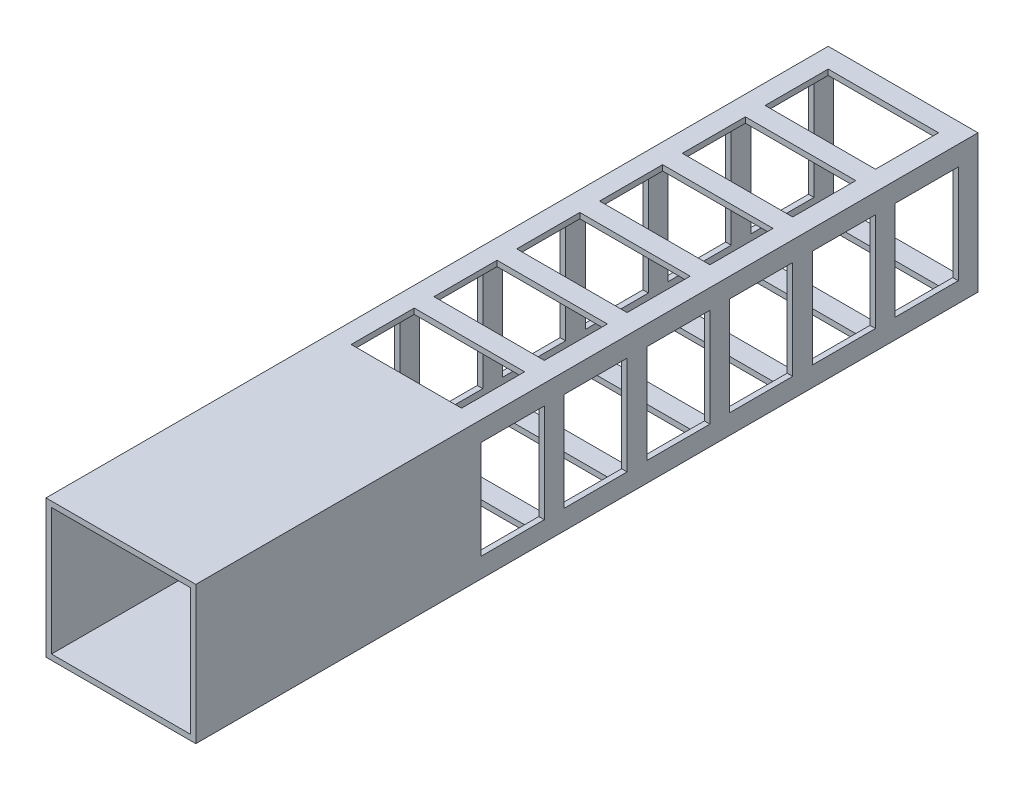
SolidWorks part; units mm, degrees
ref_plane "Front Plane" through (0, 0, 0) normal (0, 0, 1) x (1, 0, 0)
ref_plane "Top Plane" through (0, 0, 0) normal (0, 1, 0) x (1, 0, 0)
ref_plane "Right Plane" through (0, 0, 0) normal (1, 0, 0) x (0, 0, -1)
sketch "Sketch1" plane through (0, 0, 0) normal (0, 0, 1) x (1, 0, 0)
  line L0 (-88, 87.5) -> (88, 87.5)
  line L1 (-95, 94.5) -> (95, 94.5)
  line L2 (-95, 94.5) -> (-95, -80.5)
  line L3 (-95, -80.5) -> (95, -80.5)
  line L4 (95, 94.5) -> (95, -80.5)
  line L5 (88, 87.5) -> (88, -73.5)
  line L6 (-88, -73.5) -> (88, -73.5)
  line L7 (-88, 87.5) -> (-88, -73.5)
  dimension "D3" = 7
extrude "Boss-Extrude1" add sketch "Sketch1" along normal mid plane 992
ref_plane "Plane1" through (95, 0, 0) normal (1, 0, 0) x (0, 0, -1)
sketch "Sketch2" plane through (95, 0, 0) normal (1, 0, 0) x (0, 0, -1)
  line L0 (-496, -80.5) -> (496, -80.5) construction
  line L1 (391, 69.5) -> (471, 69.5)
  line L2 (391, 69.5) -> (391, -55.5)
  line L3 (391, -55.5) -> (471, -55.5)
  line L4 (471, 69.5) -> (471, -55.5)
  line L5 (496, -80.5) -> (496, 94.5) construction
  line L6 (286, 69.5) -> (286, -55.5)
  line L7 (286, 69.5) -> (366, 69.5)
  line L8 (366, 69.5) -> (366, -55.5)
  line L9 (286, -55.5) -> (366, -55.5)
  line L10 (181, 69.5) -> (181, -55.5)
  line L11 (181, 69.5) -> (261, 69.5)
  line L12 (261, 69.5) -> (261, -55.5)
  line L13 (181, -55.5) -> (261, -55.5)
  line L14 (76, 69.5) -> (76, -55.5)
  line L15 (76, 69.5) -> (156, 69.5)
  line L16 (156, 69.5) -> (156, -55.5)
  line L17 (76, -55.5) -> (156, -55.5)
  line L18 (-29, 69.5) -> (-29, -55.5)
  line L19 (-29, 69.5) -> (51, 69.5)
  line L20 (51, 69.5) -> (51, -55.5)
  line L21 (-29, -55.5) -> (51, -55.5)
  line L22 (-134, 69.5) -> (-134, -55.5)
  line L23 (-134, 69.5) -> (-54, 69.5)
  line L24 (-54, 69.5) -> (-54, -55.5)
  line L25 (-134, -55.5) -> (-54, -55.5)
  line L26 (391, 69.5) -> (286, 69.5) construction
  dimension "D1" = 125
  dimension "D2" = 80
  dimension "D3" = 25
  dimension "D4" = 25
  dimension "D6" = 105
  dimension "D5" = 6
extrude "Cut-Extrude1" cut sketch "Sketch2" against normal through all
ref_plane "Plane2" through (0, 94.5, 0) normal (0, 1, 0) x (1, 0, 0)
sketch "Sketch5" plane through (0, 94.5, 0) normal (0, 1, 0) x (1, 0, 0)
  line L0 (-95, -496) -> (-95, 496) construction
  line L1 (-70, 471) -> (70, 471)
  line L2 (-70, 471) -> (-70, 391)
  line L3 (-70, 391) -> (70, 391)
  line L4 (70, 471) -> (70, 391)
  line L5 (95, 496) -> (-95, 496) construction
  line L6 (-70, 286) -> (70, 286)
  line L7 (-70, 366) -> (70, 366)
  line L8 (70, 366) -> (70, 286)
  line L9 (-70, 366) -> (-70, 286)
  line L10 (-70, 181) -> (70, 181)
  line L11 (-70, 261) -> (70, 261)
  line L12 (70, 261) -> (70, 181)
  line L13 (-70, 261) -> (-70, 181)
  line L14 (-70, 76) -> (70, 76)
  line L15 (-70, 156) -> (70, 156)
  line L16 (70, 156) -> (70, 76)
  line L17 (-70, 156) -> (-70, 76)
  line L18 (-70, -29) -> (70, -29)
  line L19 (-70, 51) -> (70, 51)
  line L20 (70, 51) -> (70, -29)
  line L21 (-70, 51) -> (-70, -29)
  line L22 (-70, -134) -> (70, -134)
  line L23 (-70, -54) -> (70, -54)
  line L24 (70, -54) -> (70, -134)
  line L25 (-70, -54) -> (-70, -134)
  dimension "D1" = 80
  dimension "D2" = 140
  dimension "D3" = 25
  dimension "D4" = 25
  dimension "D5" = 6
extrude "Cut-Extrude2" cut sketch "Sketch5" against normal through all
